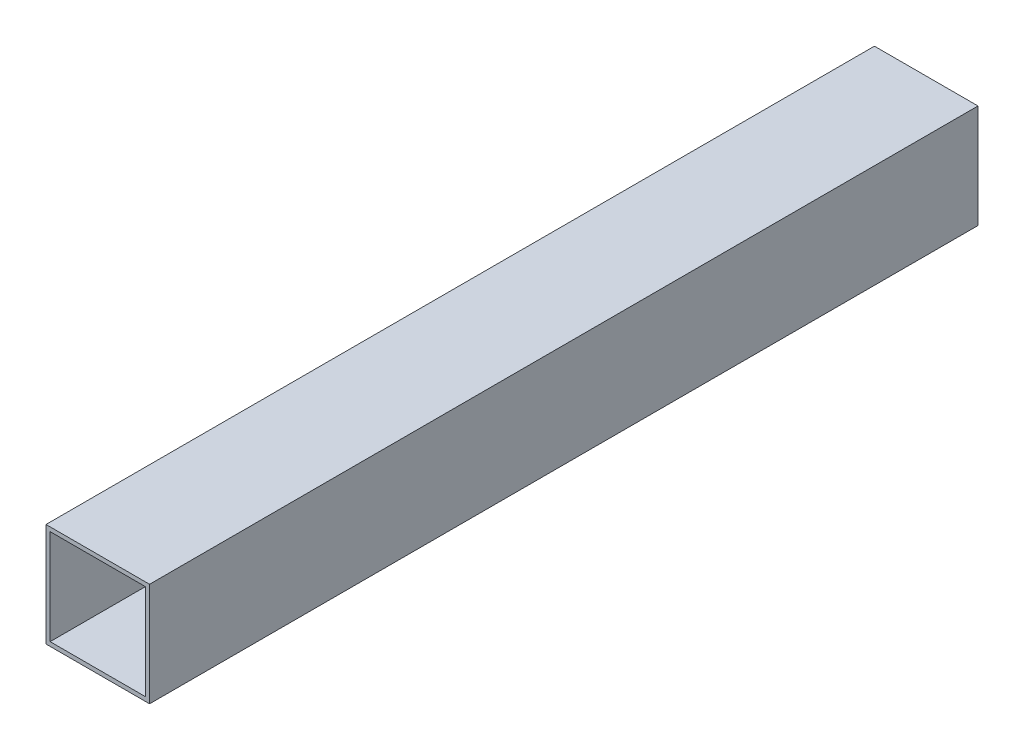
SolidWorks part; units mm, degrees
ref_plane "Plano frontal" through (0, 0, 0) normal (0, 0, 1) x (1, 0, 0)
ref_plane "Plano superior" through (0, 0, 0) normal (0, 1, 0) x (1, 0, 0)
ref_plane "Plano direito" through (0, 0, 0) normal (1, 0, 0) x (0, 0, -1)
sketch "Esboço1" plane through (0, 0, 0) normal (0, 0, 1) x (1, 0, 0)
  line L0 (2, 2) -> (2, 48)
  line L1 (0, 0) -> (50, 0)
  line L2 (0, 0) -> (0, 50)
  line L3 (0, 50) -> (50, 50)
  line L4 (50, 0) -> (50, 50)
  line L9 (2, 48) -> (48, 48)
  line L10 (48, 2) -> (48, 48)
  line L11 (2, 2) -> (48, 2)
  dimension "D1" = 50
  dimension "D2" = 50
  dimension "D3" = 2
extrude "Ressalto-extrusão1" add sketch "Esboço1" along normal blind 400
